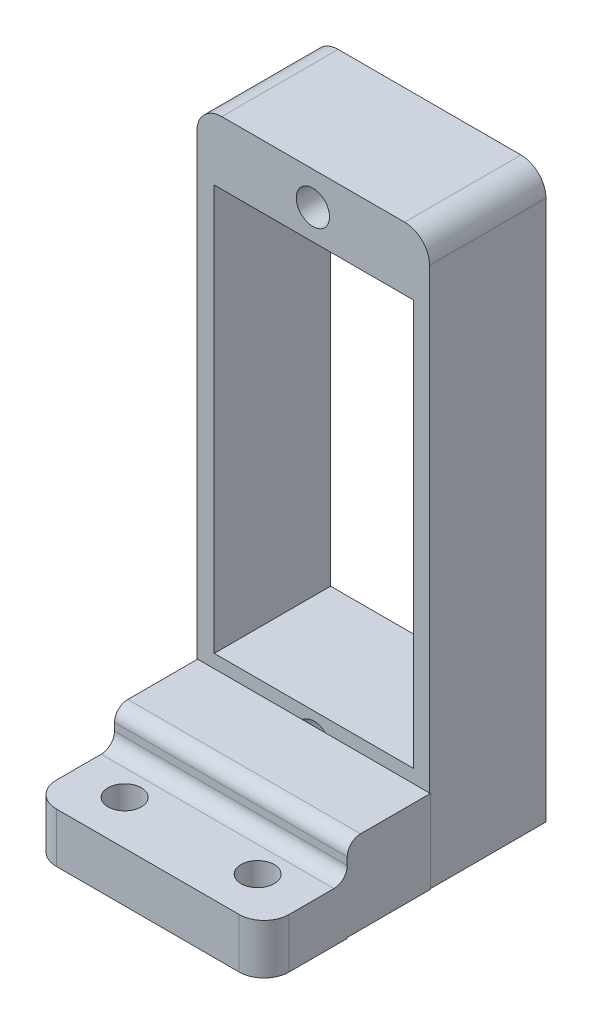
SolidWorks part; units mm, degrees
ref_plane "Front Plane" through (0, 0, 0) normal (0, 0, 1) x (1, 0, 0)
ref_plane "Top Plane" through (0, 0, 0) normal (0, 1, 0) x (1, 0, 0)
ref_plane "Right Plane" through (0, 0, 0) normal (1, 0, 0) x (0, 0, -1)
other "Graphic1"
ref_plane "Plane1" through (0, 0, 25) normal (0, 0, 1) x (1, 0, 0)
sketch "Sketch1" plane through (0, 0, 25) normal (0, 0, 1) x (1, 0, 0)
  line L1 (231.953, 496.9906) -> (245.953, 496.9906)
  line L2 (231.953, 496.9906) -> (231.953, 462.9906)
  line L3 (231.953, 462.9906) -> (245.953, 462.9906)
  line L4 (245.953, 496.9906) -> (245.953, 462.9906)
  dimension "D1" = 14
  dimension "D2" = 34
extrude "Boss-Extrude1" add sketch "Sketch1" along normal blind 7
sketch "Sketch2" plane through (0, 0, 32) normal (0, 0, 1) x (1, 0, 0)
  line L1 (233, 493.2) -> (245, 493.2)
  line L2 (233, 493.2) -> (233, 468.8)
  line L3 (233, 468.8) -> (245, 468.8)
  line L4 (245, 493.2) -> (245, 468.8)
  circle A0 centre (238.9351, 495.0031) radius 1
  dimension "D1" = 12
  dimension "D2" = 24.4
extrude "Cut-Extrude1" cut sketch "Sketch2" against normal through all
sketch "Sketch3" plane through (0, 0, 32) normal (0, 0, 1) x (1, 0, 0)
  line L1 (232, 468) -> (246, 468)
  line L2 (232, 468) -> (232, 463)
  line L3 (232, 463) -> (246, 463)
  line L4 (246, 468) -> (246, 463)
  dimension "D1" = 14
  dimension "D2" = 5
extrude "Boss-Extrude2" add sketch "Sketch3" along normal blind 5
sketch "Sketch4" plane through (0, 0, 37) normal (0, 0, 1) x (1, 0, 0)
  line L1 (232, 465.9467) -> (246, 465.9467)
  line L2 (232, 465.9467) -> (232, 462.9467)
  line L3 (232, 462.9467) -> (246, 462.9467)
  line L4 (246, 465.9467) -> (246, 462.9467)
  dimension "D1" = 14
  dimension "D2" = 3
extrude "Boss-Extrude3" add sketch "Sketch4" along normal blind 5
fillet "Fillet1" radius 1.5 4 edges at (232, 464.4467, 42) (246, 464.4467, 42) (231.953, 496.9906, 28.5) (245.953, 496.9906, 28.5)
fillet "Fillet2" radius 0.8 2 edges at (239, 465.9467, 37) (239, 468, 37)
sketch "Sketch5" plane through (0, 0, 25) normal (0, 0, -1) x (-1, 0, 0)
  line L0 (-238.9964, 468.8) -> (-238.9964, 461.5771) construction
  circle A0 centre (-238.9964, 467.2725) radius 1
extrude "Cut-Extrude2" cut sketch "Sketch5" against normal blind 7
sketch "Sketch6" plane through (0, 465.9467, 0) normal (0, 1, 0) x (1, 0, 0)
  circle A0 centre (234.9515, -39.3412) radius 1
  circle A1 centre (242.9515, -39.3412) radius 1
  dimension "D1" = 8
extrude "Cut-Extrude3" cut sketch "Sketch6" against normal through all
